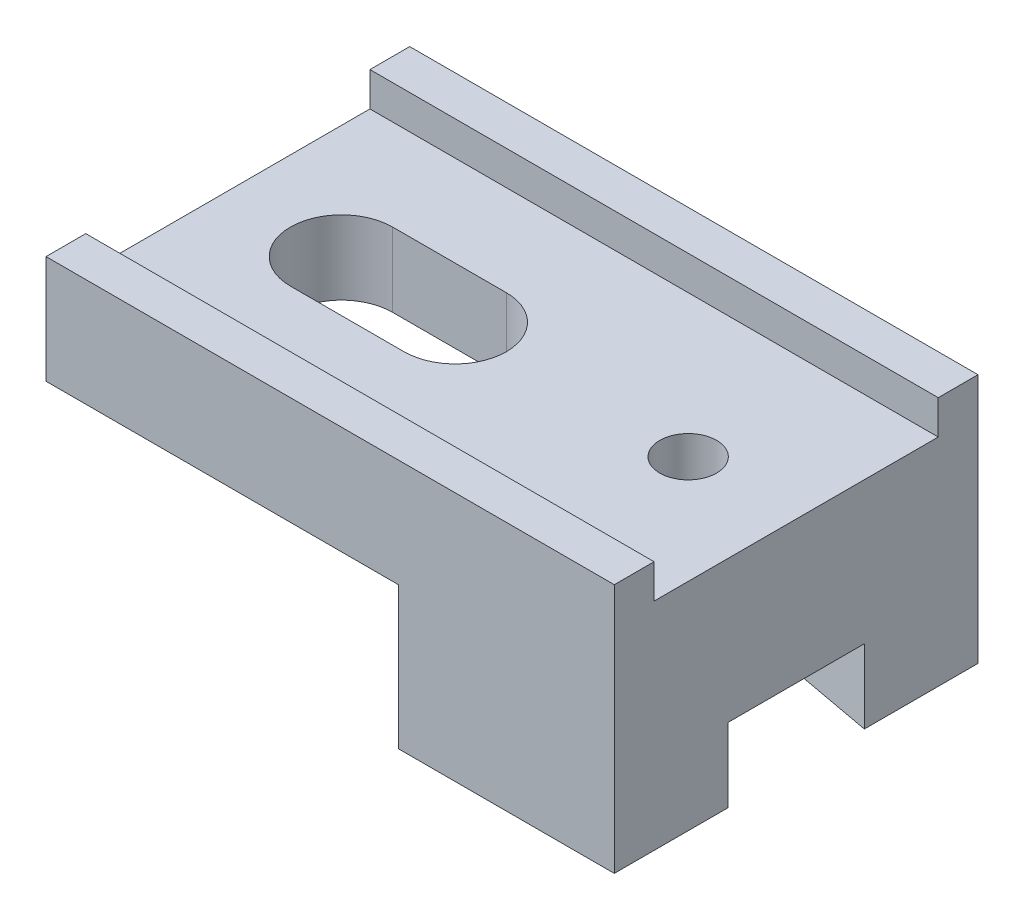
SolidWorks part; units mm, degrees
ref_plane "Alzado" through (0, 0, 0) normal (0, 0, 1) x (1, 0, 0)
ref_plane "Planta" through (0, 0, 0) normal (0, 1, 0) x (1, 0, 0)
ref_plane "Vista lateral" through (0, 0, 0) normal (1, 0, 0) x (0, 0, -1)
sketch "Croquis1" plane through (0, 0, 0) normal (0, 1, 0) x (1, 0, 0)
  line L1 (0, 0) -> (100, 0)
  line L2 (0, 0) -> (0, -64)
  line L3 (0, -64) -> (100, -64)
  line L4 (100, 0) -> (100, -64)
  dimension "D1" = 64
  dimension "D2" = 100
extrude "Saliente-Extruir1" add sketch "Croquis1" along normal blind 19
sketch "Croquis2" plane through (0, 0, 0) normal (-1, 0, 0) x (0, 0, 1)
  line L0 (0, 19) -> (64, 19) construction
  line L1 (57, 24.9137) -> (7, 24.9137)
  line L2 (57, 24.9137) -> (57, 13)
  line L3 (57, 13) -> (7, 13)
  line L4 (7, 24.9137) -> (7, 13)
  line L5 (64, 19) -> (64, 0) construction
  line L6 (0, 19) -> (0, 0) construction
  dimension "D1" = 6
  dimension "D2" = 7
  dimension "D3" = 50
  dimension "D4" = 7
extrude "Cortar-Extruir1" cut sketch "Croquis2" against normal through all
sketch "Croquis3" plane through (0, 0, 0) normal (0, -1, 0) x (-1, 0, 0)
  line L0 (-100, -64) -> (-62, -64)
  line L1 (0, -64) -> (-100, -64) construction
  line L2 (-62, -64) -> (-62, 0)
  line L3 (-100, 0) -> (0, 0) construction
  line L4 (-62, 0) -> (-100, 0)
  line L5 (-100, 0) -> (-100, -64)
  dimension "D1" = 38
extrude "Saliente-Extruir2" add sketch "Croquis3" along normal blind 25
sketch "Croquis4" plane through (0, -25, 0) normal (0, -1, 0) x (1, 0, 0)
  line L0 (100, 44) -> (100, 20)
  line L1 (100, 0) -> (100, 64) construction
  line L2 (100, 20) -> (62, 13)
  line L3 (62, 64) -> (62, 0) construction
  line L4 (62, 13) -> (62, 51)
  line L5 (62, 51) -> (100, 44)
  dimension "D1" = 24
  dimension "D2" = 38
  dimension "D3" = 20
  dimension "D4" = 13
  dimension "D5" = 24
extrude "Cortar-Extruir3" cut sketch "Croquis4" against normal blind 13
sketch "Croquis5" plane through (0, -12, 0) normal (0, -1, 0) x (-1, 0, 0)
  line L0 (-62, -51) -> (-62, -13) construction
  circle A0 centre (-81, -32) radius 5
  point P4 (-62, -32)
  dimension "D1" = 10
  dimension "D2" = 19
extrude "Cortar-Extruir4" cut sketch "Croquis5" against normal through all
sketch "Croquis6" plane through (0, -25, 0) normal (0, -1, 0) x (-1, 0, 0)
  line L0 (-100, -44) -> (-100, -64) construction
  line L1 (-100, -64) -> (-62, -64) construction
  line L2 (-62, 0) -> (-100, 0) construction
  line L3 (-100, 0) -> (-100, -20) construction
  circle A0 centre (-87, -10) radius 3
  circle A1 centre (-87, -54) radius 3
  dimension "D1" = 13
  dimension "D2" = 10
  dimension "D3" = 10
  dimension "D4" = 13
  dimension "D5" = 6
  dimension "D6" = 6
extrude "Cortar-Extruir5" cut sketch "Croquis6" against normal blind 20
sketch "Croquis7" plane through (0, 0, 0) normal (0, -1, 0) x (-1, 0, 0)
  line L0 (-40, -32) -> (-20, -32) construction
  line L1 (-40, -23) -> (-20, -23)
  line L2 (-40, -41) -> (-20, -41)
  line L3 (-62, -51) -> (-62, -13) construction
  line L4 (-62, 0) -> (0, 0) construction
  arc A0 (-40, -23) -> (-40, -41) centre (-40, -32) ccw
  arc A1 (-20, -41) -> (-20, -23) centre (-20, -32) ccw
  point P2 (-30, -32)
  point P7 (-49, -32)
  point P8 (-11, -32)
  dimension "D1" = 9
  dimension "D2" = 38
  dimension "D3" = 13
  dimension "D4" = 32
extrude "Cortar-Extruir6" cut sketch "Croquis7" against normal through all
